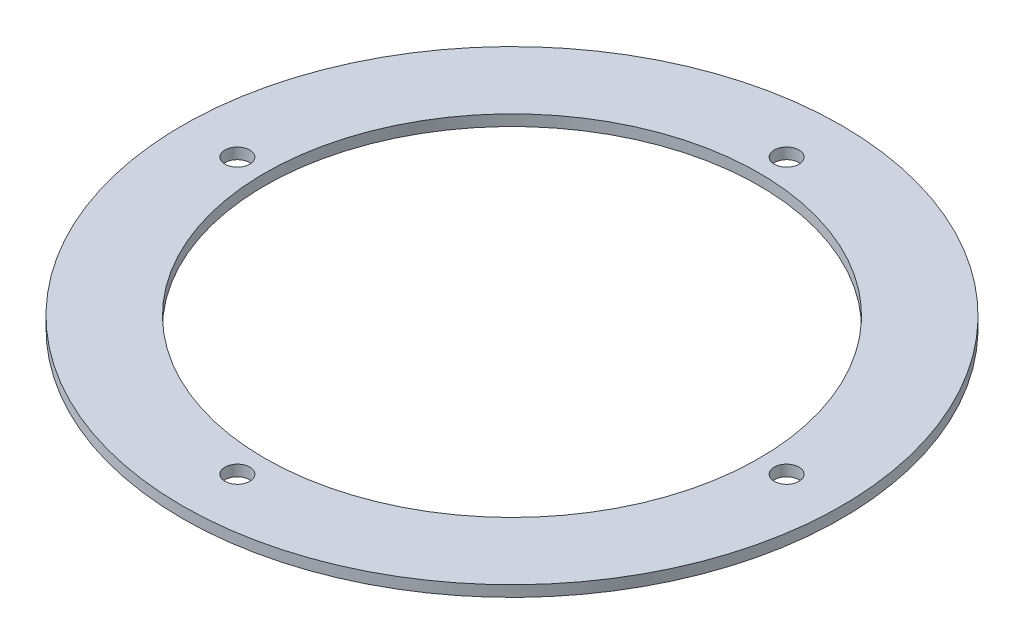
SolidWorks part; units mm, degrees
material "1060 Alloy"
ref_plane "Front Plane" through (0, 0, 0) normal (0, 0, 1) x (1, 0, 0)
ref_plane "Top Plane" through (0, 0, 0) normal (0, 1, 0) x (1, 0, 0)
ref_plane "Right Plane" through (0, 0, 0) normal (1, 0, 0) x (0, 0, -1)
sketch "Sketch1" plane through (0, 0, 0) normal (0, 1, 0) x (1, 0, 0)
  circle A0 centre (0, 0) radius 60
  circle A1 centre (0, 0) radius 45
  circle A2 centre (0, 0) radius 50 construction
  circle A3 centre (0, 50) radius 2.25
  circle A4 centre (50, 0) radius 2.25
  circle A5 centre (0, -50) radius 2.25
  circle A6 centre (-50, 0) radius 2.25
  point P16 (0, 0)
  dimension "D1" = 120
  dimension "D2" = 90
  dimension "D3" = 100
  dimension "D4" = 4.5
  dimension "D5" = 4
extrude "Boss-Extrude1" add sketch "Sketch1" along normal blind 2
